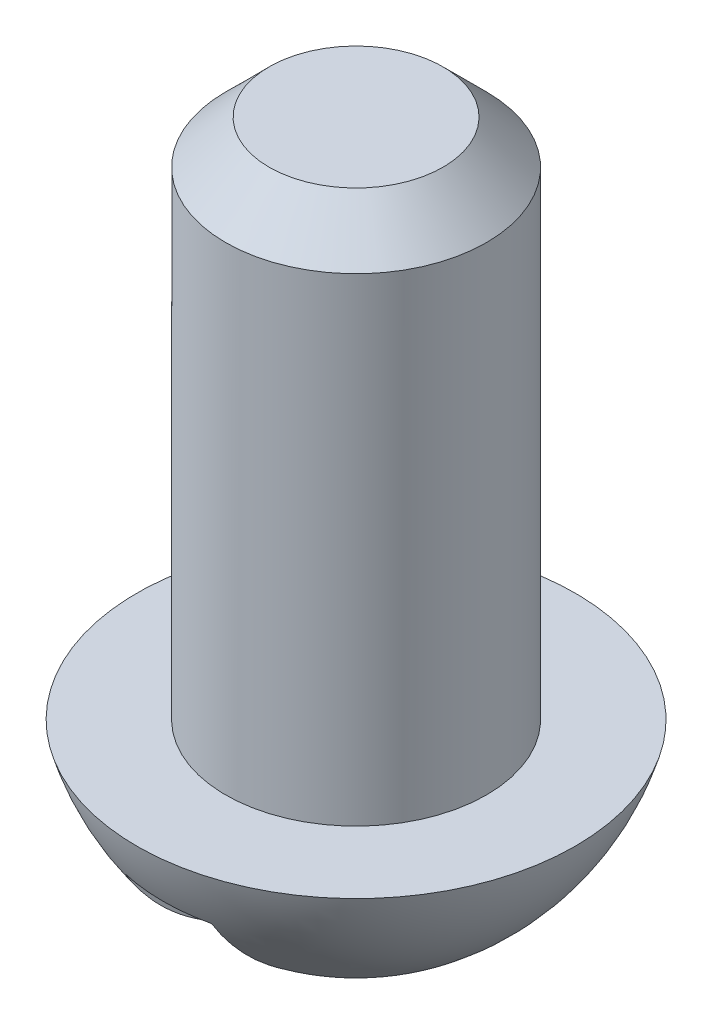
SolidWorks part; units mm, degrees
material "Plain Carbon Steel"
ref_plane "Спереди" through (0, 0, 0) normal (0, 0, 1) x (1, 0, 0)
ref_plane "Сверху" through (0, 0, 0) normal (0, 1, 0) x (1, 0, 0)
ref_plane "Справа" through (0, 0, 0) normal (1, 0, 0) x (0, 0, -1)
sketch "Sketch1" plane through (0, 0, 0) normal (0, 1, 0) x (1, 0, 0)
  circle A0 centre (0, 0) radius 1.5
  dimension "D1" = 3
extrude "Boss-Extrude1" add sketch "Sketch1" along normal blind 6
sketch "Sketch2" plane through (0, 0, 0) normal (0, 0, 1) x (1, 0, 0)
  line L0 (0, 0) -> (-2.52, 0)
  line L1 (0, -2.1) -> (0, 0) construction
  line L2 (0, 0) -> (0, -2.1)
  arc A0 (-2.52, 0) -> (0, -2.1) centre (0.2711, 0.7873) ccw
  dimension "D3" = 2.9
  dimension "D1" = 2.52
  dimension "D2" = 2.1
revolve "Revolve1" add sketch "Sketch2" angle 360 about L1
sketch "Sketch3" plane through (0, 0, 0) normal (0, 0, 1) x (1, 0, 0)
  line L0 (-0.5, -0.7) -> (0, -0.7)
  line L1 (0, -0.7) -> (0.5, -0.7)
  line L2 (0.5, -0.7) -> (0.5, -4.6381)
  line L3 (0.5, -4.6381) -> (-0.5, -4.6381)
  line L4 (-0.5, -4.6381) -> (-0.5, -0.7)
  dimension "D1" = 0.7
  dimension "D2" = 1
extrude "Cut-Extrude1" cut sketch "Sketch3" against normal through all and the other way through all
chamfer "Chamfer1" distance 0.5 angle 45 1 edges at (0, 6, 1.5)
